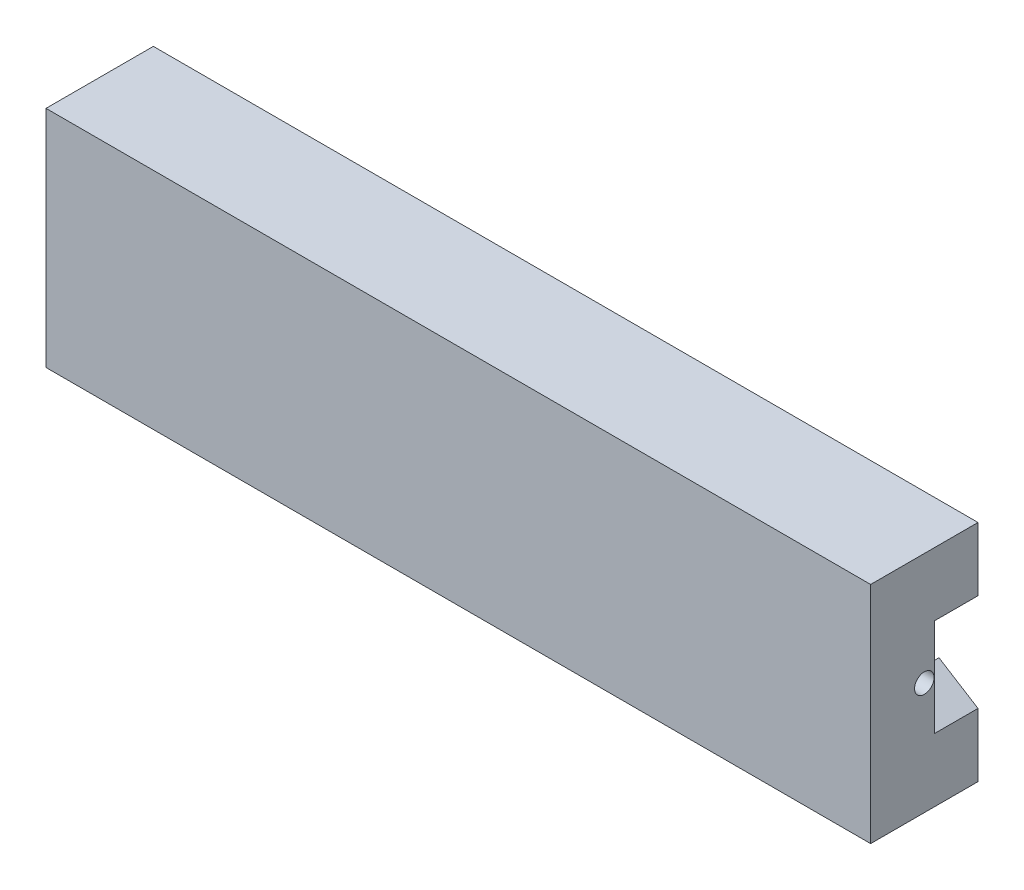
SolidWorks part; units mm, degrees
ref_plane "Front Plane" through (0, 0, 0) normal (0, 0, 1) x (1, 0, 0)
ref_plane "Top Plane" through (0, 0, 0) normal (0, 1, 0) x (1, 0, 0)
ref_plane "Right Plane" through (0, 0, 0) normal (1, 0, 0) x (0, 0, -1)
sketch "Sketch1" plane through (0, 0, 0) normal (0, 0, 1) x (1, 0, 0)
  line L1 (38.25, 7.5) -> (-38.25, 7.5)
  line L2 (38.25, 7.5) -> (38.25, -7.5)
  line L3 (38.25, -7.5) -> (-38.25, -7.5)
  line L4 (-38.25, 7.5) -> (-38.25, -7.5)
  line L5 (38.25, 7.5) -> (-38.25, -7.5) construction
  line L6 (38.25, -7.5) -> (-38.25, 7.5) construction
  point P0 (0, 0)
  dimension "D1" = 76.5
  dimension "D2" = 15
extrude "Boss-Extrude1" add sketch "Sketch1" along normal blind 3
sketch "Sketch2" plane through (38.25, 0, 0) normal (1, 0, 0) x (0, 0, -1)
  line L0 (-1.5, 7.5) -> (-1.5, -7.5) construction
  line L1 (-3, 7.5) -> (0, 7.5) construction
  line L2 (-3, -7.5) -> (0, -7.5) construction
  line L3 (-1.5, -7.5) -> (0, 0) construction
  line L4 (0, -7.5) -> (0, 7.5) construction
  line L5 (0, 0) -> (-1.5, 0) construction
  circle A0 centre (-1.5, 0) radius 1
  dimension "D1" = 2
extrude "Cut-Extrude1" cut sketch "Sketch2" against normal through all
sketch "Sketch3" plane through (0, 0, 0) normal (0, 0, -1) x (-1, 0, 0)
  line L8 (42.25, -11.5) -> (42.25, 11.5)
  line L9 (42.25, 11.5) -> (-42.25, 11.5)
  line L10 (-42.25, 11.5) -> (-42.25, -11.5)
  line L11 (-42.25, -11.5) -> (42.25, -11.5)
  line L12 (42.25, -11.5) -> (42.25, 11.5)
  line L13 (42.25, 11.5) -> (-42.25, 11.5)
  line L14 (-42.25, 11.5) -> (-42.25, -11.5)
  line L15 (-42.25, -11.5) -> (42.25, -11.5)
  dimension "D1" = 4
extrude "Boss-Extrude2" add sketch "Sketch3" against normal offset from surface (7 mm away) 4 separate body up to face at (0, 0, 3) offset beyond the face yes
combine bodies "Combine1" operation type subtract main body 103 bodies to subtract 102
sketch "Sketch4" plane through (38.25, 0, 0) normal (-1, 0, 0) x (0, 0, 1)
  circle A0 centre (1.5, 0) radius 1 construction
  circle A1 centre (1.5, 0) radius 1
extrude "Cut-Extrude2" cut sketch "Sketch4" against normal through all and the other way through all
sketch "Sketch5" plane through (0, 0, 0) normal (0, 0, -1) x (-1, 0, 0)
  line L2 (-38.25, -7.5) -> (-38.25, 7.5) construction
  line L3 (-38.25, 7.5) -> (38.25, 7.5) construction
  line L4 (-42.25, -11.5) -> (42.25, -11.5)
  line L5 (42.25, -11.5) -> (42.25, 11.5)
  line L6 (42.25, 11.5) -> (-42.25, 11.5)
  line L7 (-42.25, 11.5) -> (-42.25, -11.5)
  line L8 (-42.25, -11.5) -> (42.25, -11.5)
  line L9 (42.25, -11.5) -> (42.25, 11.5)
  line L10 (42.25, 11.5) -> (-42.25, 11.5)
  line L11 (-42.25, 11.5) -> (-42.25, -11.5)
  line L12 (38.25, -7.5) -> (-38.25, -7.5) construction
  line L13 (38.25, 7.5) -> (38.25, -7.5) construction
  line L14 (-38.25, -7.5) -> (-38.25, 7.5)
  line L15 (-38.25, 7.5) -> (38.25, 7.5)
  line L16 (38.75, -8) -> (38.75, 8)
  line L17 (-38.75, -8) -> (38.75, -8)
  line L18 (38.75, 8) -> (-38.75, 8)
  line L19 (-38.75, 8) -> (-38.75, -8)
  line L20 (38.75, -8) -> (38.75, 8)
  line L21 (-38.75, -8) -> (38.75, -8)
  line L22 (38.75, 8) -> (-38.75, 8)
  line L23 (-38.75, 8) -> (-38.75, -8)
  line L24 (38.25, -7.5) -> (-38.25, -7.5)
  line L25 (38.25, 7.5) -> (38.25, -7.5)
  line M13 (-38.25, 7.5) -> (38.25, 7.5)
  line M14 (38.25, 7.5) -> (38.25, -7.5)
  line M15 (38.25, -7.5) -> (-38.25, -7.5)
  line M16 (-38.25, -7.5) -> (-38.25, 7.5)
  dimension "D1" = 0
  dimension "D2" = 0.5
extrude "Cut-Extrude4" cut sketch "Sketch5" against normal blind 0.48 contours L22 L23 L21 L20 M16 M13 M14 M15
sketch "Sketch10" plane through (0, 0, 0) normal (0, 0, -1) x (-1, 0, 0)
  line L4 (38.25, -7.5) -> (38.25, 7.5)
  line L5 (38.25, 7.5) -> (-38.25, 7.5)
  line L6 (-38.25, 7.5) -> (-38.25, -7.5)
  line L7 (-38.25, -7.5) -> (38.25, -7.5)
  line L8 (38.25, -7.5) -> (38.25, 7.5)
  line L9 (38.25, 7.5) -> (-38.25, 7.5)
  line L10 (-38.25, 7.5) -> (-38.25, -7.5)
  line L11 (-38.25, -7.5) -> (38.25, -7.5)
  line L12 (-42.25, -11.5) -> (42.25, -11.5)
  line L13 (42.25, -11.5) -> (42.25, 11.5)
  line L14 (42.25, 11.5) -> (-42.25, 11.5)
  line L15 (-42.25, 11.5) -> (-42.25, -11.5)
  line L16 (-42.25, -11.5) -> (42.25, -11.5)
  line L17 (42.25, -11.5) -> (42.25, 11.5)
  line L18 (42.25, 11.5) -> (-42.25, 11.5)
  line L19 (-42.25, 11.5) -> (-42.25, -11.5)
  dimension "D1" = 0
  dimension "D2" = 0
extrude "Boss-Extrude7" add sketch "Sketch10" along normal blind 2
sketch "Sketch11" plane through (0, 0, -2) normal (0, 0, -1) x (-1, 0, 0)
  line L0 (-38.75, -8) -> (38.75, -8) construction
  line L1 (-38.75, 8) -> (-38.75, -8) construction
  line L2 (38.75, 8) -> (-38.75, 8) construction
  line L3 (38.75, -8) -> (38.75, 8) construction
  line L4 (38.25, -7.5) -> (38.25, 7.5)
  line L5 (38.25, 7.5) -> (-38.25, 7.5)
  line L6 (-38.25, 7.5) -> (-38.25, -7.5)
  line L7 (-38.25, -7.5) -> (38.25, -7.5)
  line L8 (38.25, -7.5) -> (38.25, 7.5)
  line L9 (38.25, 7.5) -> (-38.25, 7.5)
  line L10 (-38.25, 7.5) -> (-38.25, -7.5)
  line L11 (-38.25, -7.5) -> (38.25, -7.5)
  line L12 (-38.75, -8) -> (38.75, -8)
  line L13 (-38.75, 8) -> (-38.75, -8)
  line L14 (38.75, 8) -> (-38.75, 8)
  line L15 (38.75, -8) -> (38.75, 8)
  dimension "D1" = 0
extrude "Cut-Extrude5" cut sketch "Sketch11" against normal blind 0.45
sketch "Sketch13" plane through (0, 0, -2) normal (0, 0, -1) x (-1, 0, 0)
  line L4 (38.25, -7.5) -> (38.25, 7.5)
  line L5 (38.25, 7.5) -> (-38.25, 7.5)
  line L6 (-38.25, 7.5) -> (-38.25, -7.5)
  line L7 (-38.25, -7.5) -> (38.25, -7.5)
  line L8 (38.25, -7.5) -> (38.25, 7.5)
  line L9 (38.25, 7.5) -> (-38.25, 7.5)
  line L10 (-38.25, 7.5) -> (-38.25, -7.5)
  line L11 (-38.25, -7.5) -> (38.25, -7.5)
  line L12 (-42.25, 11.5) -> (-42.25, -11.5)
  line L13 (-42.25, -11.5) -> (42.25, -11.5)
  line L14 (42.25, -11.5) -> (42.25, 11.5)
  line L15 (42.25, 11.5) -> (-42.25, 11.5)
  line L16 (-42.25, 11.5) -> (-42.25, -11.5)
  line L17 (-42.25, -11.5) -> (42.25, -11.5)
  line L18 (42.25, -11.5) -> (42.25, 11.5)
  line L19 (42.25, 11.5) -> (-42.25, 11.5)
  dimension "D1" = 0
  dimension "D2" = 0
extrude "Boss-Extrude8" add sketch "Sketch13" along normal blind 2
sketch "Sketch14" plane through (0, 0, -4) normal (0, 0, -1) x (-1, 0, 0)
  line L0 (-42.25, 0) -> (49957.75, 0) construction
  line L1 (-42.25, 11.5) -> (-42.25, -11.5) construction
  line L2 (-42.25, -5) -> (-38.25, -2.5)
  line L3 (-38.25, 7.5) -> (-38.25, -7.5) construction
  line L4 (-38.25, -2.5) -> (-38.25, 2.5)
  line L5 (-38.25, 2.5) -> (-42.25, 5)
  line L6 (-42.25, 5) -> (-42.25, -5)
  point P4 (-42.25, 0)
  dimension "D1" = 10
  dimension "D2" = 5
  dimension "D3" = 4
extrude "Cut-Extrude6" cut sketch "Sketch14" against normal up to surface (4.48 mm away)
